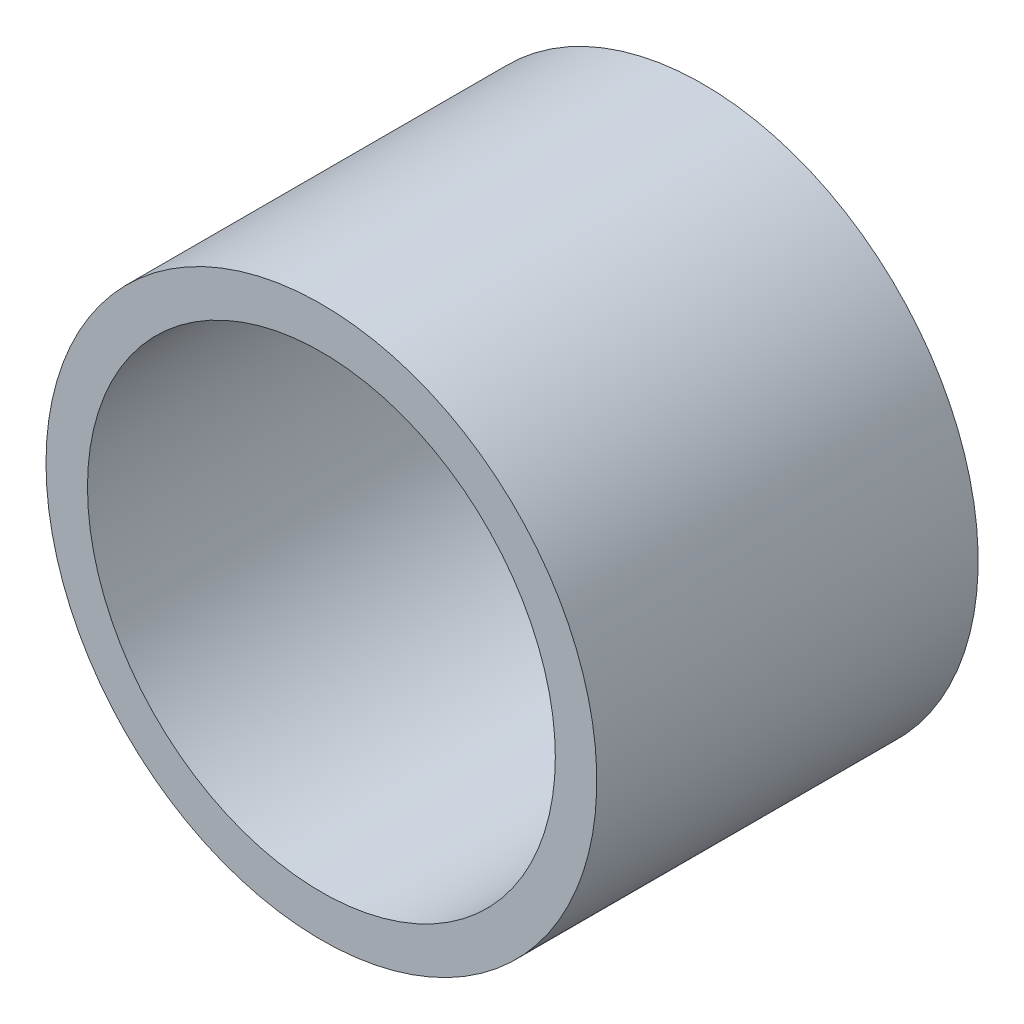
SolidWorks part; units mm, degrees
material "ABS"
ref_plane "Front Plane" through (0, 0, 0) normal (0, 0, 1) x (1, 0, 0)
ref_plane "Top Plane" through (0, 0, 0) normal (0, 1, 0) x (1, 0, 0)
ref_plane "Right Plane" through (0, 0, 0) normal (1, 0, 0) x (0, 0, -1)
sketch "Sketch1" plane through (0, 0, 0) normal (0, 0, 1) x (1, 0, 0)
  circle A0 centre (0, 0) radius 32.375
  circle A1 centre (0, 0) radius 27.5
  dimension "D1" = 64.75
  dimension "D2" = 55
extrude "Boss-Extrude1" add sketch "Sketch1" along normal blind 44.831
